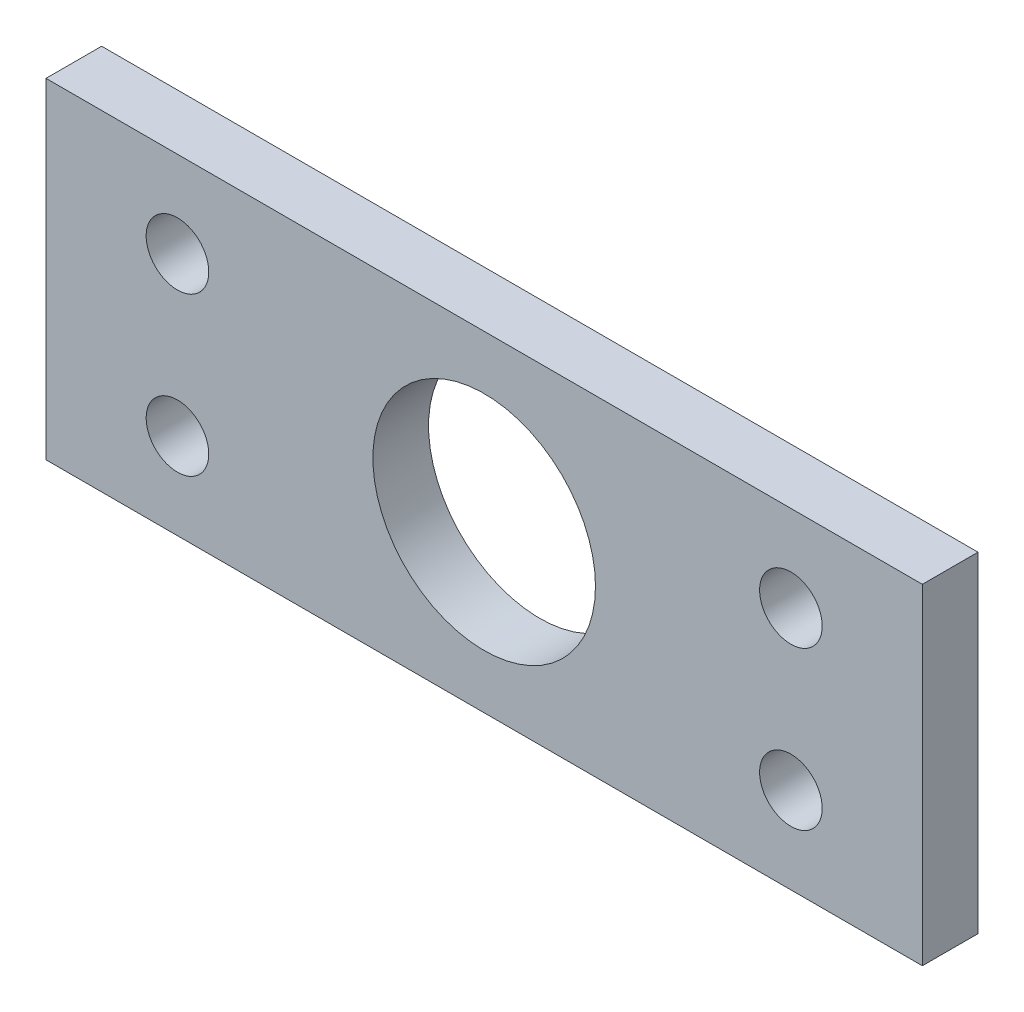
SolidWorks part; units mm, degrees
ref_plane "Alzado" through (0, 0, 0) normal (0, 0, 1) x (1, 0, 0)
ref_plane "Planta" through (0, 0, 0) normal (0, 1, 0) x (1, 0, 0)
ref_plane "Vista lateral" through (0, 0, 0) normal (1, 0, 0) x (0, 0, -1)
sketch "Croquis1" plane through (0, 0, 0) normal (0, 0, 1) x (1, 0, 0)
  line L0 (-100, 25.4) -> (100, 25.4)
  line L1 (-100, 25.4) -> (-100, -50)
  line L2 (-100, -50) -> (100, -50)
  line L3 (100, -50) -> (100, 25.4)
  line L4 (0, -50) -> (0, 25.4) construction
  circle A0 centre (0, -12.3) radius 25.4
  dimension "D1" = 50.8
extrude "Saliente-Extruir1" add sketch "Croquis1" along normal blind 12.7
sketch "Croquis2" plane through (0, 0, 12.7) normal (0, 0, 1) x (1, 0, 0)
  line L0 (-100, -12.3) -> (-70, -12.3) construction
  line L1 (-100, 25.4) -> (-100, -50) construction
  line L2 (-70, -12.3) -> (-70, 5.7) construction
  line L3 (0, -50) -> (0, -37.7) construction
  line L4 (-100, -50) -> (100, -50) construction
  line L5 (70, -12.3) -> (70, 5.7) construction
  circle A0 centre (-70, 5.7) radius 7.1438
  circle A1 centre (-70, -30.3) radius 7.1438
  circle A2 centre (0, -12.3) radius 25.4 construction
  circle A3 centre (70, -30.3) radius 7.1438
  circle A4 centre (70, 5.7) radius 7.1437
  dimension "D3" = 14.2875
  dimension "D1" = 30
  dimension "D2" = 18
extrude "Cortar-Extruir1" cut sketch "Croquis2" against normal blind 15
